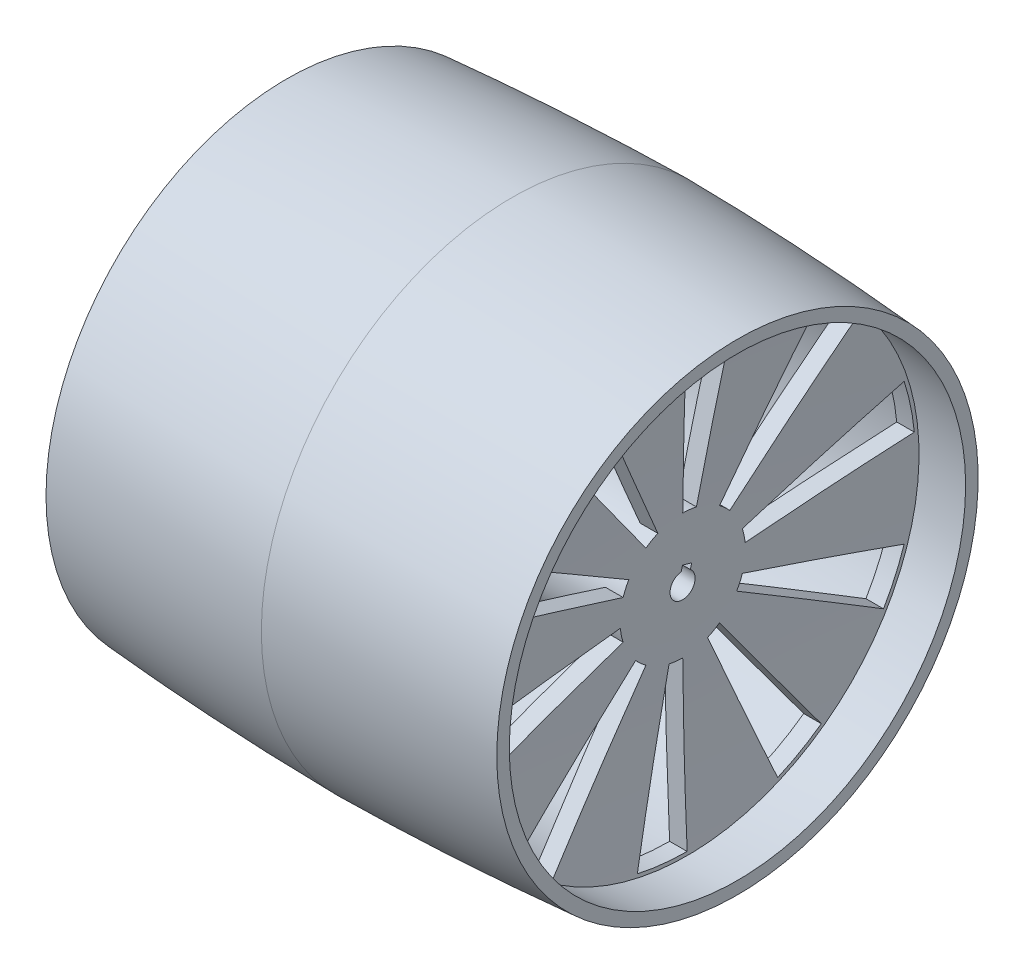
SolidWorks part; units mm, degrees
ref_plane "Front Plane" through (0, 0, 0) normal (0, 0, 1) x (1, 0, 0)
ref_plane "Top Plane" through (0, 0, 0) normal (0, 1, 0) x (1, 0, 0)
ref_plane "Right Plane" through (0, 0, 0) normal (1, 0, 0) x (0, 0, -1)
sketch "Sketch1" plane through (0, 0, 0) normal (0, 0, 1) x (1, 0, 0)
  line L0 (0, 0) -> (0, 3139.9537) construction
  line L1 (0, 0) -> (3139.9537, 0) construction
  line L2 (114.1657, 121.92) -> (114.1657, 115.57)
  line L3 (-114.1657, 121.92) -> (-114.1657, 115.57)
  line L4 (86.36, 6.35) -> (26.67, 6.35)
  line L5 (26.67, 6.35) -> (26.67, 31.75)
  line L6 (26.67, 31.75) -> (77.47, 31.75)
  spline S0 degree 2 poles (0, 127) (57.1786, 126.3709) (114.1657, 121.92) knots 0 0 0 1 1 1
  spline S1 degree 3 poles (0, 120.65) (26.6564, 120.3567) (53.2817, 119.4405) (79.8757, 117.9012) knots 0 0 0 0 0.699294 0.699294 0.699294 0.699294
  spline S2 degree 2 poles (0, 120.65) (-57.1786, 120.0209) (-114.1657, 115.57) knots 0 0 0 1 1 1
  spline S3 degree 2 poles (0, 127) (-57.1786, 126.3709) (-114.1657, 121.92) knots 0 0 0 1 1 1
  spline S4 degree 2 poles (88.7657, 117.3634) (86.2284, 61.8934) (86.36, 6.35) knots 0 0 0 1 1 1
  spline S5 degree 3 poles (79.8757, 117.9012) (78.4016, 78.8457) (77.5867, 64.7292) (77.47, 31.75) knots 0 0 0 0 0.886493 0.886493 0.886493 0.886493
  spline S6 degree 2 poles (88.7657, 117.3634) (101.4704, 116.5615) (114.1657, 115.57) knots 0.777226 0.777226 0.777226 1 1 1
  dimension "D4" = 114.3
  dimension "D1" = 127
  dimension "D2" = 124.46
  dimension "D3" = 121.92
  dimension "D5" = 6.35
  dimension "D6" = 6.35
  dimension "D7" = 6.35
  dimension "D8" = 25.4
  dimension "D9" = 87.63
  dimension "D10" = 86.36
  dimension "D11" = 76.2
  dimension "D12" = 6.35
  dimension "D13" = 28.7504
  dimension "D14" = 8.89
  dimension "D15" = 8.89
  dimension "D16" = 8.89
  dimension "D17" = 86.36
  dimension "D18" = 50.8
  dimension "D19" = 25.4
revolve "Revolve1" add sketch "Sketch1" angle 360 about L1
sketch "Sketch4" plane through (-114.1657, 0, 0) normal (-1, 0, 0) x (0, 0, 1)
  line L0 (0, 31.75) -> (0, 115.57)
  line L1 (-25.2462, 112.7788) -> (-6.9358, 30.9832)
  circle A0 centre (0, 0) radius 31.75 construction
  arc A1 (0, 31.75) -> (-6.9358, 30.9832) centre (0, 0) ccw
  circle A2 centre (0, 0) radius 115.57 construction
  arc A3 (0, 115.57) -> (-25.2462, 112.7788) centre (0, 0) ccw
  dimension "D1" = 25.4
  dimension "D2" = 6.978
extrude "Cut-Extrude2" cut sketch "Sketch4" against normal through all
pattern_circular "CirPattern2" count 10 over 360 about axis through (0, 0, 0) along (1, 0, 0) of "Cut-Extrude2"
sketch "Sketch5" plane through (26.67, 0, 0) normal (-1, 0, 0) x (0, 0, 1)
  line L0 (-4.6469, 7.5788) -> (-3.9184, 4.9969)
  line L1 (0, 8.89) -> (0.7285, 6.3081)
  line L2 (2.2054, -5.9547) -> (3.0875, -8.3366) construction
  line L3 (-4.6469, 7.5788) -> (0, 8.89)
  circle A0 centre (0, 0) radius 6.35 construction
  arc A1 (0.7285, 6.3081) -> (2.2054, -5.9547) centre (0, 0) ccw
  circle M4 centre (0, 0) radius 6.35
  dimension "D1" = 90
  dimension "D2" = 90
  dimension "D3" = 2.54
extrude "Cut-Extrude3" cut sketch "Sketch5" against normal through all contours L3 L0 L1 M4
